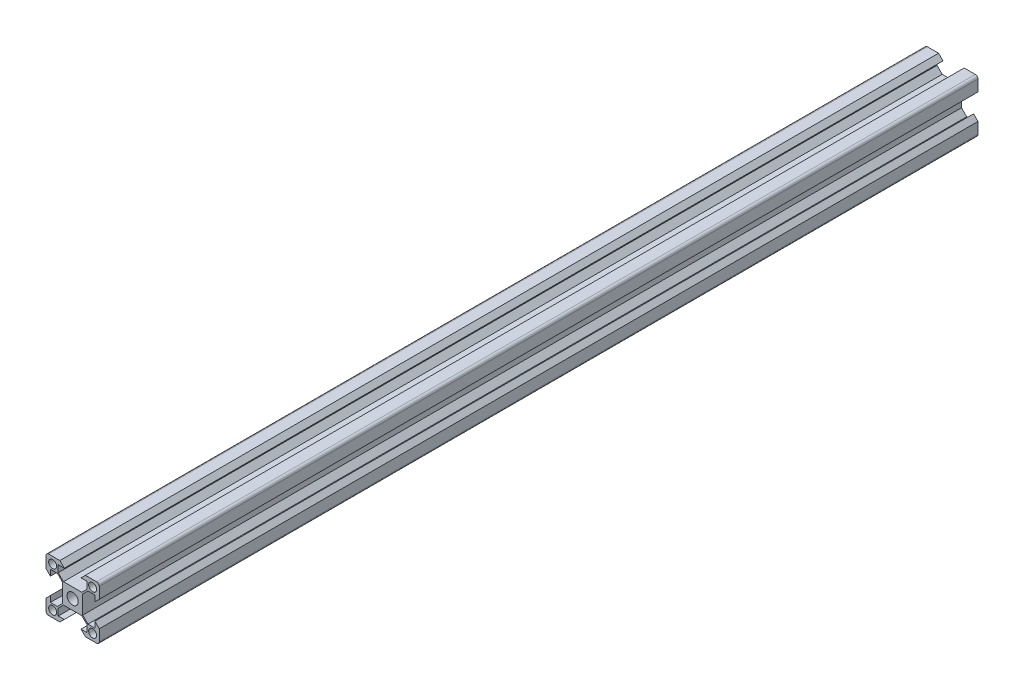
SolidWorks part; units mm, degrees
material "铝管"
ref_plane "前视基准面" through (0, 0, 0) normal (0, 0, 1) x (1, 0, 0)
ref_plane "上视基准面" through (0, 0, 0) normal (0, 1, 0) x (1, 0, 0)
ref_plane "右视基准面" through (0, 0, 0) normal (1, 0, 0) x (0, 0, -1)
sketch "草图1" plane through (0, 0, 0) normal (0, 0, 1) x (1, 0, 0)
  line L0 (0, 0) -> (-40.5659, 40.5659) construction
  line L1 (0, 0) -> (0, 75.5033) construction
  line L2 (-10, 10) -> (-10, 4.8)
  line L3 (-10, 4.8) -> (-8.34, 3.14)
  line L4 (-8.34, 3.14) -> (-8.34, 5.4)
  line L5 (-5.7536, 5.4) -> (-3.8, 3.4464)
  line L6 (-3.8, 3.4464) -> (-3.8, -3.4464)
  line L7 (-3.8, 0) -> (15.6715, 0) construction
  line L8 (-5.4, 8.34) -> (-5.4, 5.7536)
  line L9 (-3.4464, 3.8) -> (3.4464, 3.8)
  line L10 (-5.4, 5.7536) -> (-3.4464, 3.8)
  line L11 (-3.14, 8.34) -> (-5.4, 8.34)
  line L12 (-8.34, 5.4) -> (-5.7536, 5.4)
  line L13 (-4.8, 10) -> (-3.14, 8.34)
  line L14 (-10, 10) -> (-4.8, 10)
  line L15 (-10, -10) -> (-4.8, -10)
  line L16 (-4.8, -10) -> (-3.14, -8.34)
  line L17 (-8.34, -5.4) -> (-5.7536, -5.4)
  line L18 (-3.14, -8.34) -> (-5.4, -8.34)
  line L19 (-5.4, -5.7536) -> (-3.4464, -3.8)
  line L20 (-3.4464, -3.8) -> (3.4464, -3.8)
  line L21 (-5.4, -8.34) -> (-5.4, -5.7536)
  line L22 (-5.7536, -5.4) -> (-3.8, -3.4464)
  line L23 (-8.34, -3.14) -> (-8.34, -5.4)
  line L24 (-10, -4.8) -> (-8.34, -3.14)
  line L25 (-10, -10) -> (-10, -4.8)
  line L26 (10, -10) -> (10, -4.8)
  line L27 (10, -4.8) -> (8.34, -3.14)
  line L28 (8.34, -3.14) -> (8.34, -5.4)
  line L29 (5.7536, -5.4) -> (3.8, -3.4464)
  line L30 (5.4, -8.34) -> (5.4, -5.7536)
  line L31 (5.4, -5.7536) -> (3.4464, -3.8)
  line L32 (3.14, -8.34) -> (5.4, -8.34)
  line L33 (8.34, -5.4) -> (5.7536, -5.4)
  line L34 (4.8, -10) -> (3.14, -8.34)
  line L35 (10, -10) -> (4.8, -10)
  line L36 (10, 10) -> (4.8, 10)
  line L37 (4.8, 10) -> (3.14, 8.34)
  line L38 (8.34, 5.4) -> (5.7536, 5.4)
  line L39 (3.14, 8.34) -> (5.4, 8.34)
  line L40 (5.4, 5.7536) -> (3.4464, 3.8)
  line L41 (5.4, 8.34) -> (5.4, 5.7536)
  line L42 (3.8, 3.4464) -> (3.8, -3.4464)
  line L43 (5.7536, 5.4) -> (3.8, 3.4464)
  line L44 (8.34, 3.14) -> (8.34, 5.4)
  line L45 (10, 4.8) -> (8.34, 3.14)
  line L46 (10, 10) -> (10, 4.8)
  circle A0 centre (-7.5, 7.5) radius 1.5
  circle A1 centre (0, 0) radius 2.1
  circle A2 centre (-7.5, -7.5) radius 1.5
  circle A3 centre (7.5, -7.5) radius 1.5
  circle A4 centre (7.5, 7.5) radius 1.5
  point P54 (0, -3.8)
  point P64 (0, 3.8)
  dimension "D6" = 3
  dimension "D7" = 7.5
  dimension "D9" = 4.2
  dimension "D1" = 45
  dimension "D2" = 4.8
  dimension "D3" = 3.8
  dimension "D4" = 10
  dimension "D5" = 5.4
  dimension "D8" = 3.14
  dimension "D10" = 10
  dimension "D11" = 0.5
extrude "凸台-拉伸1" add sketch "草图1" along normal mid plane 330
fillet "圆角1" radius 1 4 edges at (-10, -10, 0) (10, -10, 0) (-10, 10, 0) (10, 10, 0)
